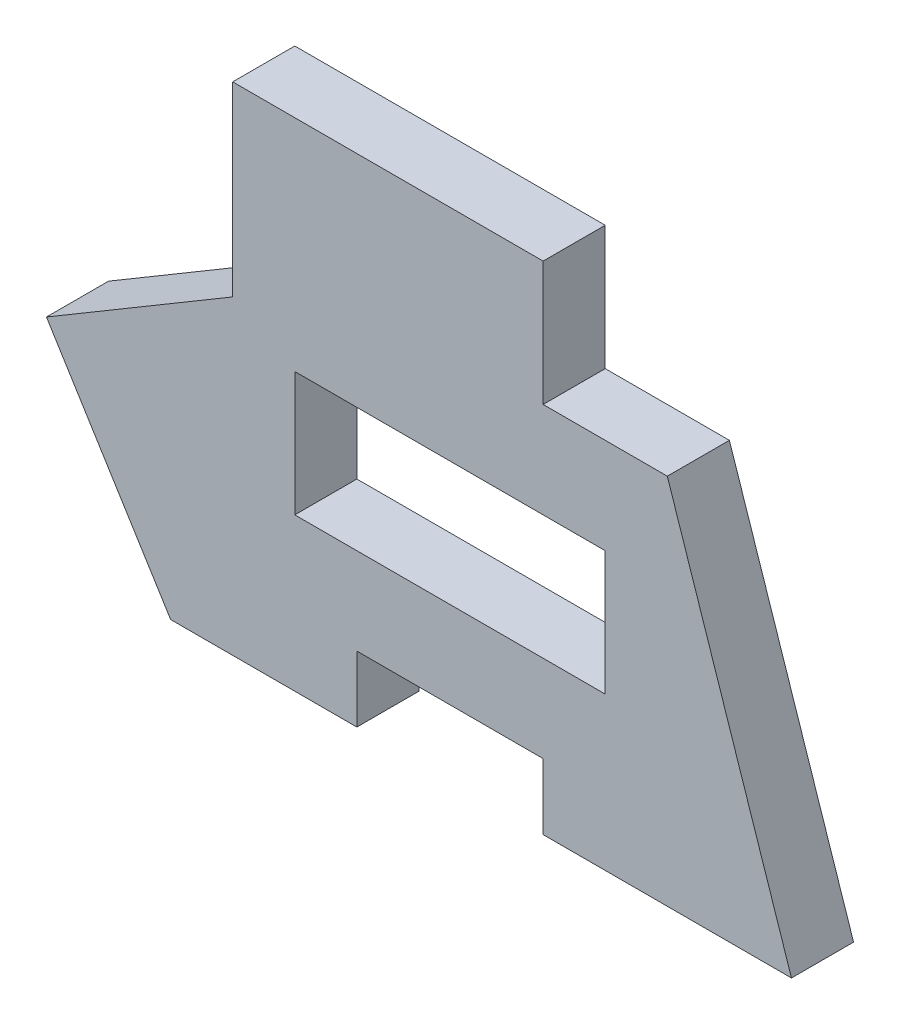
SolidWorks part; units mm, degrees
ref_plane "Front Plane" through (0, 0, 0) normal (0, 0, 1) x (1, 0, 0)
ref_plane "Top Plane" through (0, 0, 0) normal (0, 1, 0) x (1, 0, 0)
ref_plane "Right Plane" through (0, 0, 0) normal (1, 0, 0) x (0, 0, -1)
sketch "Sketch1" plane through (0, 0, 0) normal (0, 0, 1) x (1, 0, 0)
  line L0 (-275, -38.6693) -> (-175, -199.6693)
  line L1 (-175, -199.6693) -> (-25, -199.6693)
  line L3 (-125, 200.3307) -> (125, 200.3307)
  line L5 (125, -199.6693) -> (325, -199.6693)
  line L6 (125, 100.3307) -> (225, 100.3307)
  line L8 (-25, -199.6693) -> (-25, -146.6693)
  line L9 (-25, -146.6693) -> (125, -146.6693)
  line L10 (125, -146.6693) -> (125, -199.6693)
  line L14 (125, 100.3307) -> (125, 200.3307)
  line L16 (-125, 200.3307) -> (-125, 50.3307)
  line L17 (-125, 50.3307) -> (-275, -38.6693)
  line L18 (225, 100.3307) -> (325, -199.6693)
  line L20 (-75, 23.3307) -> (175, 23.3307)
  line L21 (-75, 23.3307) -> (-75, -76.6693)
  line L22 (-75, -76.6693) -> (175, -76.6693)
  line L23 (175, 23.3307) -> (175, -76.6693)
  point P0 (0, 0)
  dimension "D2" = 200
  dimension "D3" = 100
  dimension "D4" = 250
  dimension "D5" = 250
  dimension "D6" = 100
  dimension "D7" = 100
  dimension "D8" = 250
  dimension "D10" = 150
  dimension "D11" = 150
  dimension "D12" = 53
  dimension "D13" = 150
  dimension "D14" = 400
  dimension "D15" = 100
  dimension "D16" = 123
  dimension "D17" = 200
extrude "Boss-Extrude1" add sketch "Sketch1" along normal blind 50
